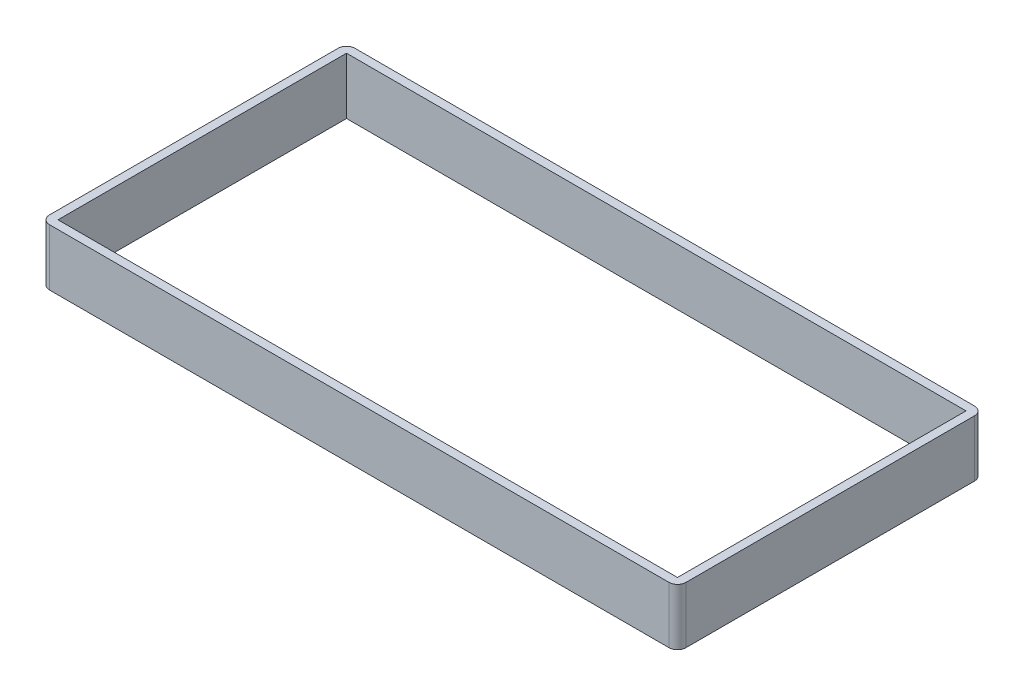
SolidWorks part; units mm, degrees
ref_plane "Front Plane" through (0, 0, 0) normal (0, 0, 1) x (1, 0, 0)
ref_plane "Top Plane" through (0, 0, 0) normal (0, 1, 0) x (1, 0, 0)
ref_plane "Right Plane" through (0, 0, 0) normal (1, 0, 0) x (0, 0, -1)
sketch "Sketch1" plane through (0, 0, 0) normal (0, 1, 0) x (1, 0, 0)
  line L0 (-109.5, 51) -> (109.5, 51)
  line L1 (-109.5, 51) -> (-109.5, -51)
  line L2 (109.5, 51) -> (109.5, -51)
  line L3 (-109.5, -51) -> (109.5, -51)
  line L4 (-109.5, 51) -> (109.5, -51) construction
  line L5 (109.5, 51) -> (-109.5, -51) construction
  point P1 (0, 0)
  dimension "D1" = 219
  dimension "D2" = 102
extrude "Extrude-Thin1" add sketch "Sketch1" along normal mid plane 20 thin thin type one direction wall 3
fillet "Fillet1" radius 3 4 edges at (-112.5, 0, -54) (-112.5, 0, 54) (112.5, 0, -54) (112.5, 0, 54)
